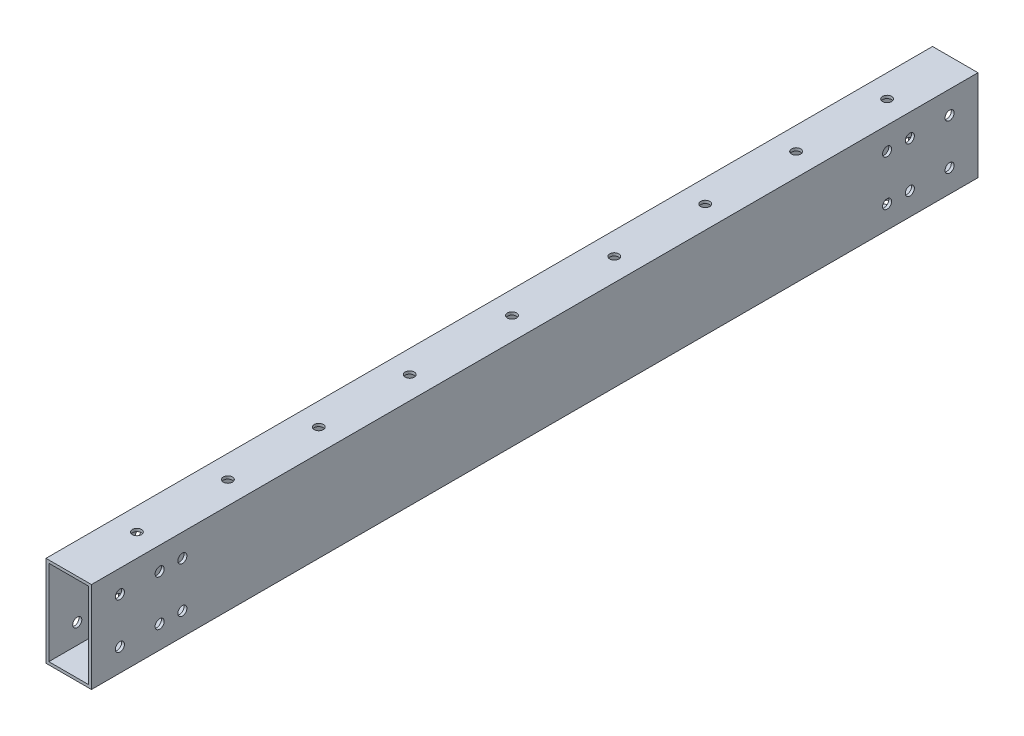
SolidWorks part; units mm, degrees
ref_plane "Front Plane" through (0, 0, 0) normal (0, 0, 1) x (1, 0, 0)
ref_plane "Top Plane" through (0, 0, 0) normal (0, 1, 0) x (1, 0, 0)
ref_plane "Right Plane" through (0, 0, 0) normal (1, 0, 0) x (0, 0, -1)
sketch "Sketch1" plane through (0, 0, 0) normal (0, 0, 1) x (1, 0, 0)
  line L0 (11.1125, -23.8125) -> (-11.1125, 23.8125) construction
  line L1 (-12.7, -25.4) -> (12.7, -25.4)
  line L2 (-12.7, -25.4) -> (-12.7, 25.4)
  line L3 (-12.7, 25.4) -> (12.7, 25.4)
  line L4 (12.7, -25.4) -> (12.7, 25.4)
  line L5 (-11.1125, -23.8125) -> (11.1125, -23.8125)
  line L6 (-11.1125, -23.8125) -> (-11.1125, 23.8125)
  line L7 (-11.1125, 23.8125) -> (11.1125, 23.8125)
  line L8 (11.1125, -23.8125) -> (11.1125, 23.8125)
  dimension "D1" = 25.4
  dimension "D2" = 50.8
  dimension "D3" = 1.5875
  dimension "D4" = 1.5875
  dimension "D5" = 1.5875
  dimension ".0625" = 1.5875
extrude "Boss-Extrude1" add sketch "Sketch1" along normal blind 495.3
sketch "Sketch2" plane through (12.7, 0, 0) normal (1, 0, 0) x (0, 0, -1)
  line L0 (-247.65, 25.4) -> (-247.65, -25.4) construction
  line L1 (-495.3, 0) -> (-479.425, 0) construction
  line L2 (-495.3, -25.4) -> (0, -25.4) construction
  line L3 (-479.425, 12.7) -> (-479.425, -12.7) construction
  line L4 (-495.3, 25.4) -> (0, 25.4) construction
  line L5 (-495.3, -25.4) -> (-495.3, 25.4) construction
  circle A5 centre (-479.425, -12.7) radius 2.54
  circle A6 centre (-457.2, -12.7) radius 2.54
  circle A7 centre (-479.425, 12.7) radius 2.54
  circle A8 centre (-457.2, 12.7) radius 2.54
  circle A9 centre (-38.1, 12.7) radius 2.54
  circle A10 centre (-15.875, 12.7) radius 2.54
  circle A11 centre (-38.1, -12.7) radius 2.54
  circle A12 centre (-15.875, -12.7) radius 2.54
  circle A13 centre (-444.5, 12.7) radius 2.54
  circle A14 centre (-444.5, -12.7) radius 2.54
  circle A15 centre (-50.8, -12.7) radius 2.54
  circle A16 centre (-50.8, 12.7) radius 2.54
  point P31 (0, 0)
  point P32 (0, 0)
  point P33 (0, 0)
  dimension "D2" = 5.08
  dimension "D3" = 12.7
  dimension "D9" = 15.875
  dimension "D10" = 38.1
  dimension "D11" = 12.7
extrude "Cut-Extrude1" cut sketch "Sketch2" against normal through all
sketch "Sketch3" plane through (0, 25.4, 0) normal (0, 1, 0) x (1, 0, 0)
  line L0 (12.7, -247.65) -> (-12.7, -247.65) construction
  line L1 (12.7, -495.3) -> (12.7, 0) construction
  line L2 (-12.7, -495.3) -> (-12.7, 0) construction
  line L3 (12.7, -495.3) -> (-12.7, -495.3) construction
  circle A0 centre (0, -457.2) radius 2.54
  circle A1 centre (0, -406.4) radius 2.54
  circle A2 centre (0, -355.6) radius 2.54
  circle A3 centre (0, -304.8) radius 2.54
  circle A6 centre (0, -190.5) radius 2.54
  circle A7 centre (0, -139.7) radius 2.54
  circle A8 centre (0, -88.9) radius 2.54
  circle A9 centre (0, -38.1) radius 2.54
  circle A10 centre (0, -247.65) radius 2.54
  dimension "D3" = 5.08
  dimension "D1" = 12.7
  dimension "D2" = 38.1
  dimension "D4" = 4
extrude "Cut-Extrude2" cut sketch "Sketch3" against normal through all
